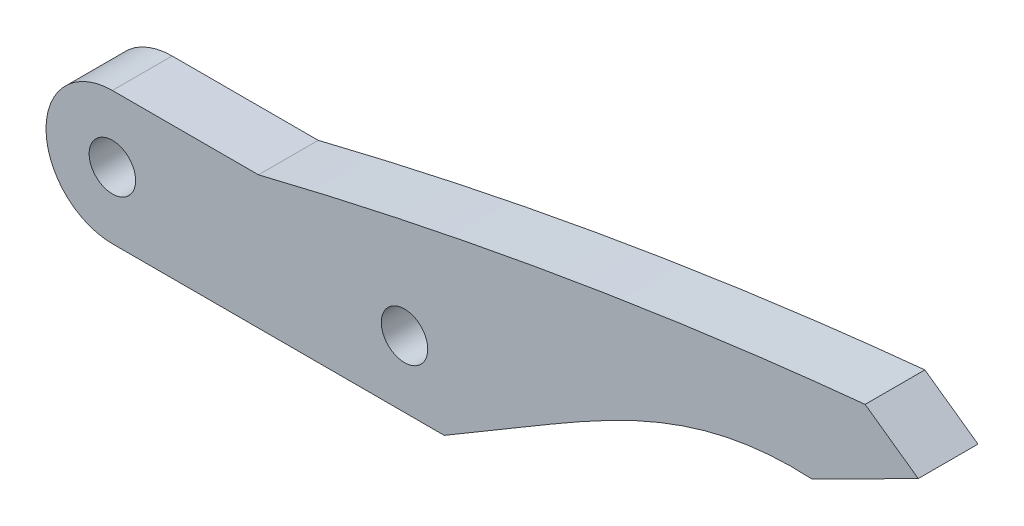
SolidWorks part; units mm, degrees
ref_plane "Front Plane" through (0, 0, 0) normal (0, 0, 1) x (1, 0, 0)
ref_plane "Top Plane" through (0, 0, 0) normal (0, 1, 0) x (1, 0, 0)
ref_plane "Right Plane" through (0, 0, 0) normal (1, 0, 0) x (0, 0, -1)
sketch "Sketch2" plane through (0, 0, 0) normal (0, 0, 1) x (1, 0, 0)
  line L0 (-11, 0) -> (11, 0) construction
  line L2 (-16, 5) -> (16, 5)
  line L3 (-16, 5) -> (-16, -5)
  line L4 (-16, -5) -> (16, -5)
  line L5 (16, 5) -> (16, -5)
  line L6 (-16, 5) -> (16, -5) construction
  line L7 (-16, -5) -> (16, 5) construction
  circle A0 centre (-11, 0) radius 1.75
  circle A1 centre (-11, 0) radius 5
  circle A2 centre (11, 0) radius 1.75
  circle A3 centre (11, 0) radius 5
  point P3 (0, 0)
  point P4 (0, 0)
  dimension "D2" = 3.5
  dimension "D3" = 10
  dimension "D4" = 3.5
  dimension "D5" = 10
  dimension "D1" = 22
extrude "Boss-Extrude1" add sketch "Sketch2" along normal blind 4.5 contours A1 A0 | A3 A2 | A3 L2 A1 L4
sketch "Sketch3" plane through (0, 0, 4.5) normal (0, 0, 1) x (1, 0, 0)
  line L0 (45.689, 12.87) -> (49.689, 10.03)
  line L1 (49.689, 10.03) -> (41.689, 6)
  line L2 (-11, -5) -> (11, -5) construction
  line L3 (11, 0) -> (11, -5) construction
  line L4 (19.9421, -1.48) -> (13.99, -5)
  line L5 (13.99, -5) -> (11, -5)
  line L6 (-11, 5) -> (11, 5) construction
  line L7 (0, 5) -> (-0.7935, 5)
  line L8 (-11, 5) -> (11, 5)
  arc A1 (11, -5) -> (11, 5) centre (11, 0) ccw construction
  arc A2 (11, -5) -> (11, 5) centre (11, 0) ccw
  spline S0 degree 3 poles (41.689, 6) (33.2855, 6.4595) (26.9184, 2.6457) (19.9421, -1.48) knots 0 0 0 0 1 1 1 1
  spline S1 degree 2 poles (0, 5) (22.5643, 10.5903) (45.689, 12.87) knots 0 0 0 1 1 1
  arc M4 (11, -5) -> (11, 5) centre (11, 0) ccw
  line M5 (11, 5) -> (-11, 5)
  dimension "D1" = 4
  dimension "D2" = 8
  dimension "D3" = 17.87
  dimension "D4" = 15.03
  dimension "D5" = 11
  dimension "D6" = 9.45
  dimension "D7" = 3.52
  dimension "D8" = 9.61
  dimension "D9" = 20.52
  dimension "D10" = 31.27
  dimension "D11" = 2.99
  dimension "D12" = 13.52
  dimension "D13" = 15.07
extrude "Boss-Extrude2" add sketch "Sketch3" against normal blind 4.5 contours S1 L5 L4 S0 L1 L0 M5 M4
